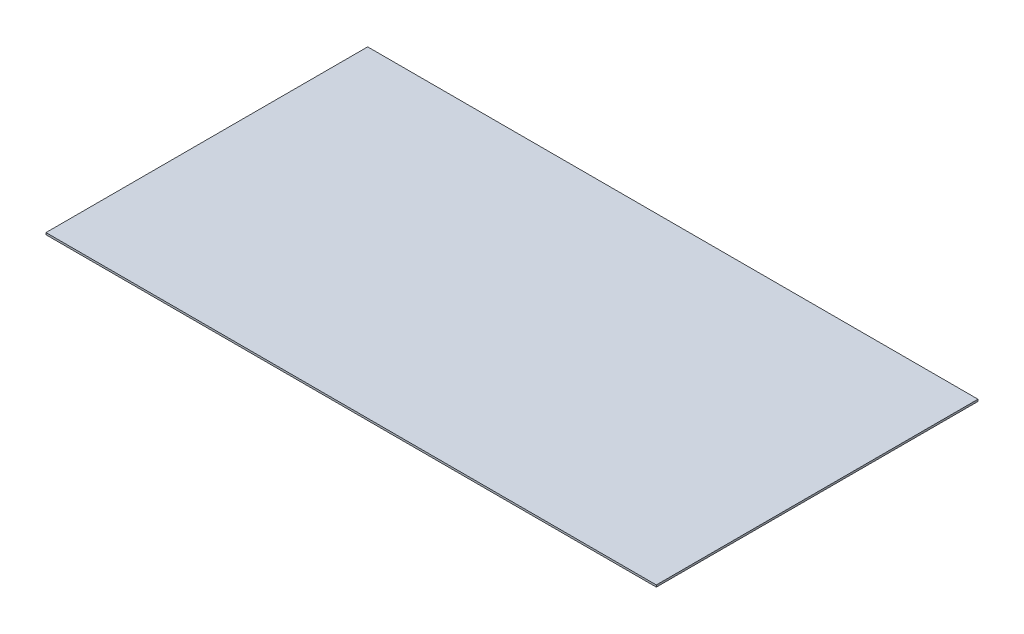
SolidWorks part; units mm, degrees
ref_plane "Front Plane" through (0, 0, 0) normal (0, 0, 1) x (1, 0, 0)
ref_plane "Top Plane" through (0, 0, 0) normal (0, 1, 0) x (1, 0, 0)
ref_plane "Right Plane" through (0, 0, 0) normal (1, 0, 0) x (0, 0, -1)
sketch "Sketch1" plane through (0, 0, 0) normal (0, 0, 1) x (1, 0, 0)
  line L0 (-187.96, 0) -> (187.96, 0) construction
  line L1 (0, -0.5969) -> (0, 0.5969) construction
  point P0 (-11.5062, 0)
  point P2 (0, 0)
  point P5 (0, 0)
  point P9 (0, 0)
  dimension "Width" = 375.92
  dimension "Wire Diameter" = 1.1938
  dimension "Opening Size" = 11.5062
sketch "Sketch2" plane through (0, 0, 0) normal (1, 0, 0) x (0, 0, -1)
  line L0 (-99.06, 0) -> (99.06, 0) construction
  point P3 (0, 0)
  dimension "Length" = 198.12
sketch "Sketch3" plane through (0, 0, 0) normal (0, 0, 1) x (1, 0, 0)
  line L1 (-187.96, -0.5969) -> (187.96, -0.5969)
  line L2 (-187.96, -0.5969) -> (-187.96, 0.5969)
  line L3 (-187.96, 0.5969) -> (187.96, 0.5969)
  line L4 (187.96, -0.5969) -> (187.96, 0.5969)
  line L5 (-187.96, -0.5969) -> (187.96, 0.5969) construction
  line L6 (-187.96, 0.5969) -> (187.96, -0.5969) construction
  point P0 (0, 0)
extrude "Boss-Extrude1" add sketch "Sketch3" along normal mid plane 198.12
sketch "Sketch4" plane through (0, 0, 0) normal (0, 1, 0) x (1, 0, 0)
  line L0 (-187.96, 0) -> (-15.367, 0) construction
  line L1 (-187.96, -99.06) -> (-187.96, 99.06) construction
  line L2 (187.96, 0) -> (15.367, 0) construction
  line L3 (187.96, -99.06) -> (187.96, 99.06) construction
  line L4 (0, 99.06) -> (0, -73.533) construction
  line L5 (187.96, 99.06) -> (-187.96, 99.06) construction
  line L6 (0, -99.06) -> (0, 73.533) construction
  line L7 (187.96, -99.06) -> (-187.96, -99.06) construction
  line L8 (-15.367, 0) -> (-15.367, 99.06) construction
  dimension "D1" = 172.593
sketch "Sketch5" plane through (0, 0, 0) normal (1, 0, 0) x (0, 0, -1)
  line L0 (-99.06, 0) -> (73.533, 0) construction
  line L1 (-99.06, -0.5969) -> (-99.06, 0.5969) construction
  line L2 (99.06, 0) -> (-73.533, 0) construction
  line L3 (99.06, -0.5969) -> (99.06, 0.5969) construction
  dimension "D1" = 172.593
sketch "Sketch6" plane through (0, 0, 0) normal (0, 1, 0) x (1, 0, 0)
  line L0 (-187.96, 99.06) -> (187.96, 99.06)
  line L1 (187.96, 99.06) -> (187.96, -99.06)
  line L2 (187.96, -99.06) -> (81.28, -99.06)
  line L3 (187.96, -99.06) -> (-187.96, -99.06) construction
  line L4 (81.28, -99.06) -> (81.28, 93.98)
  line L5 (81.28, 93.98) -> (-187.96, 93.98)
  line L6 (-187.96, -99.06) -> (-187.96, 99.06) construction
  line L7 (-187.96, 93.98) -> (-187.96, 99.06)
  dimension "D1" = 5.08
  dimension "D2" = 106.68
extrude "Cut-Extrude1" [suppressed] cut sketch "Sketch6" against normal through all both and the other way through all
equation "\"D1@Boss-Extrude1\"=\"Length@Sketch2\""
equation "\"D1@Sketch4\"=\"Opening Size@Sketch1\"*15"
equation "\"D1@Sketch5\"=\"D1@Sketch4\""
